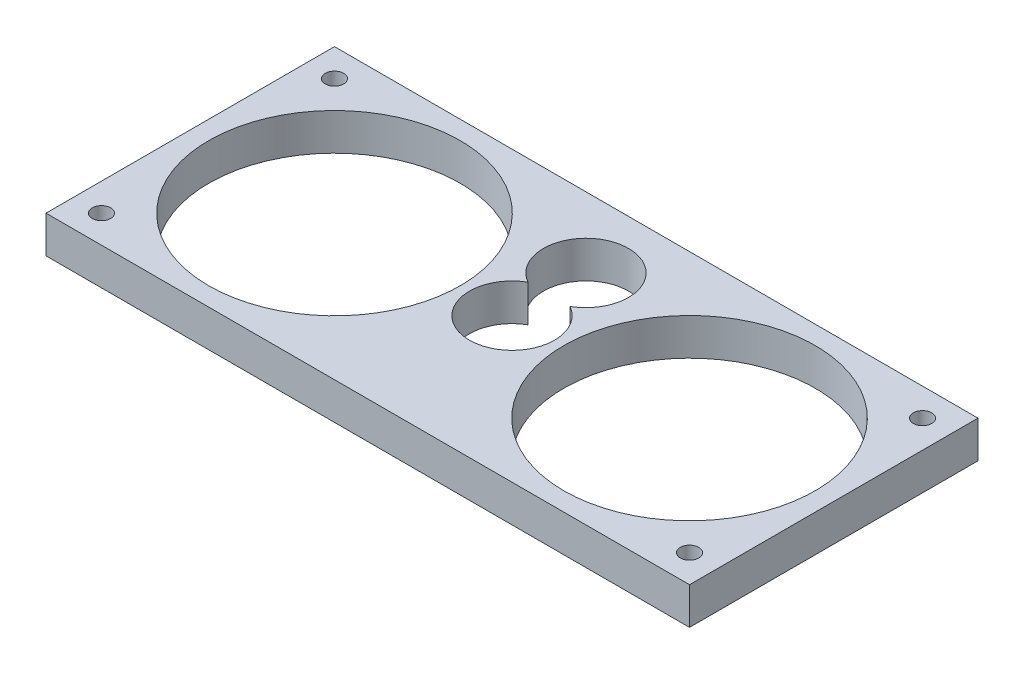
SolidWorks part; units mm, degrees
ref_plane "Front Plane" through (0, 0, 0) normal (0, 0, 1) x (1, 0, 0)
ref_plane "Top Plane" through (0, 0, 0) normal (0, 1, 0) x (1, 0, 0)
ref_plane "Right Plane" through (0, 0, 0) normal (1, 0, 0) x (0, 0, -1)
sketch "Sketch1" plane through (0, 0, 0) normal (0, 1, 0) x (1, 0, 0)
  line L0 (-87, -39) -> (87, -39)
  line L1 (-87, -39) -> (-87, 39)
  line L2 (-87, 39) -> (87, 39)
  line L3 (87, -39) -> (87, 39)
  line L4 (0, 0) -> (0, 20) construction
  circle A0 centre (48, 0) radius 34
  circle A1 centre (-48, 0) radius 34
  circle A2 centre (-79.5, 31.5) radius 2.5
  circle A3 centre (-79.5, -31.5) radius 2.5
  circle A4 centre (79.5, -31.5) radius 2.5
  circle A5 centre (79.5, 31.5) radius 2.5
  arc A6 (-5.6789, 10) -> (5.6789, 10) centre (0, 0) ccw
  arc A7 (5.6789, 10) -> (-5.6789, 10) centre (0, 20) ccw
extrude "Boss-Extrude1" add sketch "Sketch1" along normal blind 10
